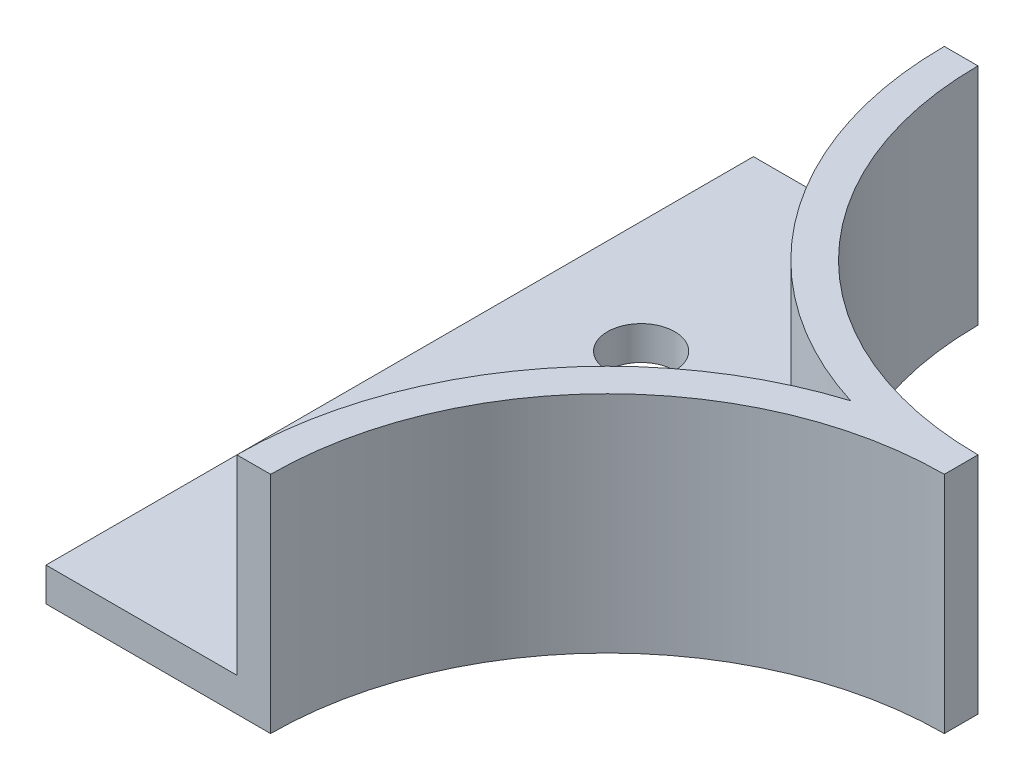
SolidWorks part; units mm, degrees
ref_plane "前基準面" through (0, 0, 0) normal (0, 0, 1) x (1, 0, 0)
ref_plane "上基準面" through (0, 0, 0) normal (0, 1, 0) x (1, 0, 0)
ref_plane "右基準面" through (0, 0, 0) normal (1, 0, 0) x (0, 0, -1)
sketch "草圖2" plane through (0, 0, 0) normal (0, 1, 0) x (1, 0, 0)
  line L0 (0, 31.5) -> (20, 31.5)
  line L1 (0, 0) -> (50, 0)
  line L2 (0, 0) -> (0, 31.5)
  line L3 (0, 31.5) -> (50, 31.5) construction
  line L4 (50, 0) -> (50, 31.5) construction
  line L5 (50, 1.5) -> (50, 0)
  circle A0 centre (50, 31.5) radius 30 construction
  arc A1 (20, 31.5) -> (50, 1.5) centre (50, 31.5) ccw
  point P5 (50, 1.5)
  point P7 (20, 31.5)
  dimension "D1" = 31.5
  dimension "D3" = 30
  dimension "D2" = 50
extrude "填料-伸長1" add sketch "草圖2" along normal blind 20
sketch "草圖3" plane through (0, 20, 0) normal (0, 1, 0) x (1, 0, 0)
  line L9 (0, 31.5) -> (17, 31.5)
  line L10 (0, 31.5) -> (0, 0)
  line L19 (0, 0) -> (40.1638, 0)
  arc A8 (17, 31.5) -> (40.1638, 0) centre (50, 31.5) ccw
  point P10 (50, 31.5)
  dimension "D2" = 33
  dimension "D1" = 3
  dimension "D3" = 40.1638
  dimension "D4" = 50
extrude "除料-伸長1" cut sketch "草圖3" against normal blind 17
sketch "草圖4" plane through (0, 3, 0) normal (0, 1, 0) x (1, 0, 0)
  line L0 (0, 31.5) -> (0, 0) construction
  line L1 (17, 31.5) -> (0, 31.5) construction
  circle A0 centre (10, 11.5) radius 3
  dimension "D1" = 6
  dimension "D3" = 10
  dimension "D5" = 20
extrude "除料-伸長2" cut sketch "草圖4" against normal through all
mirror "鏡射4" about plane through (0, 0, 0) normal (0, 0, 1) of "填料-伸長1", "除料-伸長1", "除料-伸長2"
